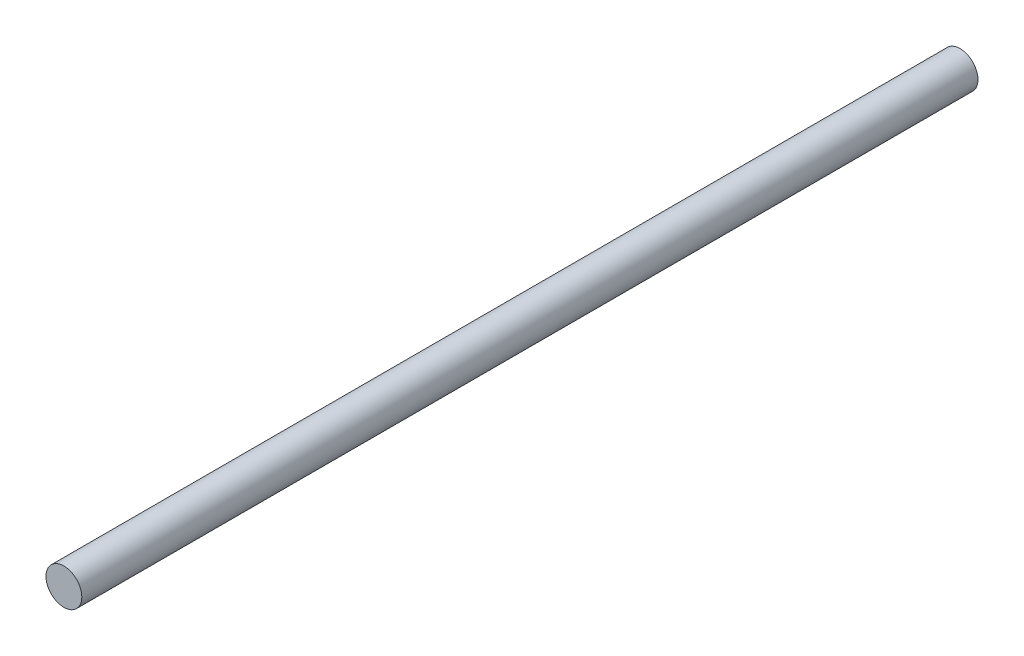
SolidWorks part; units mm, degrees
ref_plane "Front Plane" through (0, 0, 0) normal (0, 0, 1) x (1, 0, 0)
ref_plane "Top Plane" through (0, 0, 0) normal (0, 1, 0) x (1, 0, 0)
ref_plane "Right Plane" through (0, 0, 0) normal (1, 0, 0) x (0, 0, -1)
sketch "Sketch1" plane through (0, 0, 0) normal (0, 0, 1) x (1, 0, 0)
  circle A0 centre (0, 0) radius 10
  dimension "D1" = 20
extrude "Boss-Extrude1" add sketch "Sketch1" along normal blind 500
